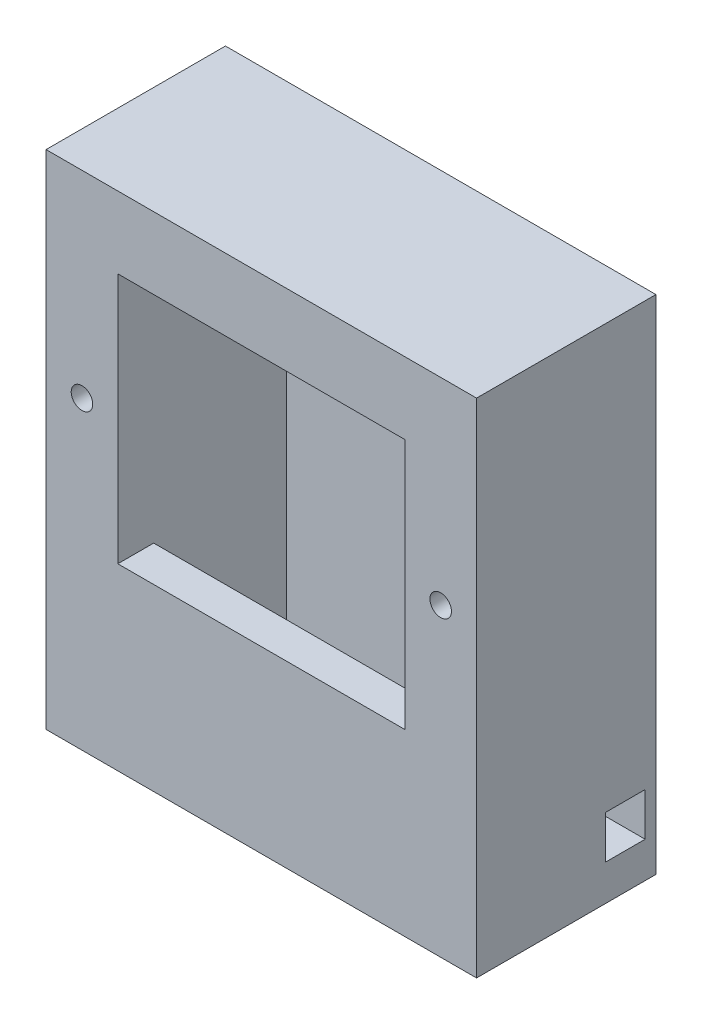
SolidWorks part; units mm, degrees
ref_plane "Front Plane" through (0, 0, 0) normal (0, 0, 1) x (1, 0, 0)
ref_plane "Top Plane" through (0, 0, 0) normal (0, 1, 0) x (1, 0, 0)
ref_plane "Right Plane" through (0, 0, 0) normal (1, 0, 0) x (0, 0, -1)
sketch "Sketch2" plane through (0, 0, 0) normal (0, 0, 1) x (1, 0, 0)
  line L1 (0, 0) -> (-120, 0)
  line L2 (0, 0) -> (0, -140)
  line L3 (0, -140) -> (-120, -140)
  line L4 (-120, 0) -> (-120, -140)
  dimension "D1" = 120
  dimension "D2" = 140
extrude "Boss-Extrude1" add sketch "Sketch2" along normal blind 50
sketch "Sketch3" plane through (0, 0, 50) normal (0, 0, 1) x (1, 0, 0)
  line L0 (0, 0) -> (-120, 0) construction
  line L1 (-100, -20) -> (-20, -20)
  line L2 (-100, -20) -> (-100, -90)
  line L3 (-100, -90) -> (-20, -90)
  line L4 (-20, -20) -> (-20, -90)
  line L5 (0, -140) -> (0, 0) construction
  line L6 (-60, -20) -> (-60, -90) construction
  line L7 (-100, -55) -> (-20, -55) construction
  circle A0 centre (-110, -55) radius 3
  circle A1 centre (-10, -55) radius 3
  dimension "D5" = 10
  dimension "D6" = 6
  dimension "D7" = 35
  dimension "D8" = 6
  dimension "D9" = 10
  dimension "D10" = 35
  dimension "D1" = 80
  dimension "D2" = 70
  dimension "D3" = 20
  dimension "D4" = 20
extrude "Cut-Extrude1" cut sketch "Sketch3" against normal blind 47
sketch "Sketch4" plane through (0, 0, 50) normal (0, 0, 1) x (1, 0, 0)
  line L0 (-120, -140) -> (0, -140) construction
  line L1 (-100, -90) -> (-20, -90)
  line L2 (-100, -90) -> (-100, -130)
  line L3 (-100, -130) -> (-20, -130)
  line L4 (-20, -90) -> (-20, -130)
  line L6 (-100, -90) -> (-20, -90) construction
  line L7 (-120, 0) -> (-120, -140) construction
  dimension "D1" = 0
  dimension "D2" = 80
  dimension "D3" = 20
  dimension "D4" = 10
extrude "Cut-Extrude3" cut sketch "Sketch4" against normal blind 37 from offset 10 offset against normal yes
sketch "Sketch5" plane through (0, 0, 0) normal (1, 0, 0) x (0, 0, -1)
  line L0 (-50, -140) -> (0, -140) construction
  line L1 (-14, -118) -> (-3, -118)
  line L2 (-14, -118) -> (-14, -130)
  line L3 (-14, -130) -> (-3, -130)
  line L4 (-3, -118) -> (-3, -130)
  line L5 (0, -140) -> (0, 0) construction
  dimension "D1" = 12
  dimension "D2" = 11
  dimension "D3" = 10
  dimension "D4" = 3
extrude "Cut-Extrude4" cut sketch "Sketch5" against normal blind 20
